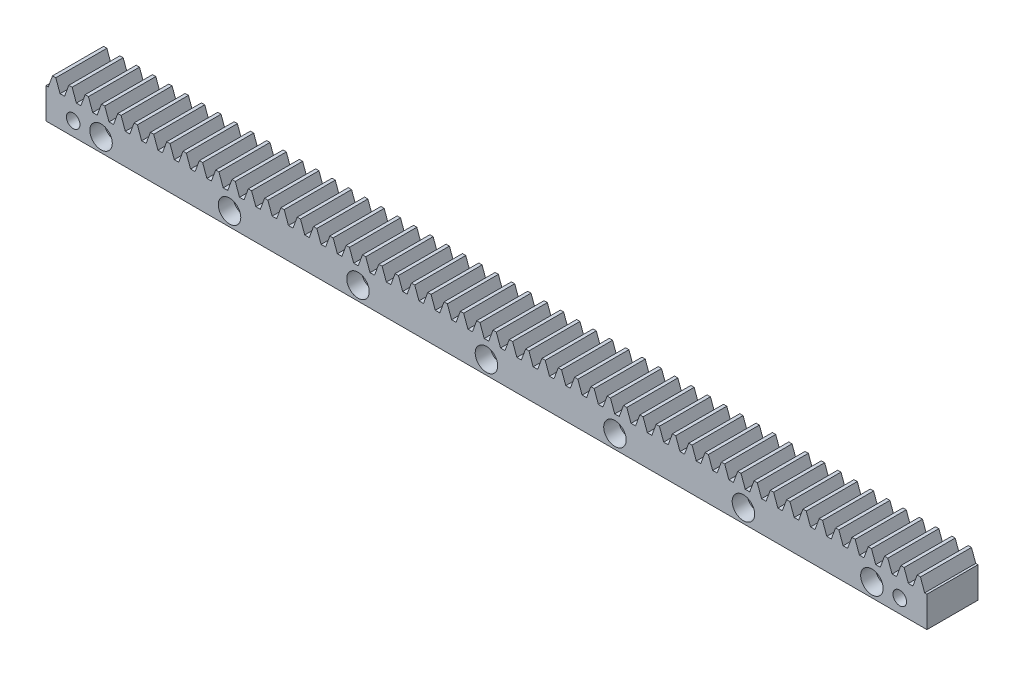
SolidWorks part; units mm, degrees
extrude "Blank" add sketch "BlankSke" against normal blind 59
sketch "BlankSke" plane through (0, 0, 0) normal (0, 0, 1) x (1, 0, 0)
  line L1 (0, 0) -> (1017.88, 0)
  line L2 (0, 0) -> (0, 49)
  line L3 (0, 49) -> (1017.88, 49)
  line L4 (1017.88, 0) -> (1017.88, 49)
  dimension "Length" = 1017.88
  dimension "Blank_height" = 49
ref_plane "Plane1" through (0, 0, 0) normal (0, 0, 1) x (1, 0, 0)
ref_plane "Plane2" through (0, 0, 0) normal (0, 1, 0) x (1, 0, 0)
ref_plane "Plane3" through (0, 0, 0) normal (1, 0, 0) x (0, 0, -1)
sketch "HoldingSke" plane through (0, 0, 0) normal (0, 1, 0) x (1, 0, 0)
  line L0 (0, 0) -> (0.0232, 0.165)
  line L1 (-15, 0) -> (100, 0) construction
  line L2 (0, 0) -> (-2.1039, 2.3779)
  line L3 (0, 0) -> (-11.863, 4.5341)
  line L4 (0, 0) -> (4.8292, 7.1596)
  line L5 (0, 0) -> (-23.7986, -8.8762)
  line L6 (0, 0) -> (-10.5278, -7.1032)
  line L9 (-71.009, 38.7566) -> (885.4854, 386.8921)
  line L10 (-76.2, 8.3779) -> (-33.2, 8.3779)
  line L11 (0, 0) -> (-59, 0)
  line L12 (-76.2, 101.6) -> (-75.993, 101.6)
  line L13 (24.9733, 27.94) -> (52.9518, 28.4284)
  line L14 (24.9733, 27.94) -> (24.9743, 27.94)
  line L15 (24.9733, 27.94) -> (100.4006, 29.5858)
  circle A0 centre (0, 0) radius 19.05
  circle A1 centre (0, 0) radius 21.5
  circle A2 centre (0, 0) radius 12.7
  dimension "MPH" = 43
  dimension "Diameter" = 38.1
  dimension "Num_teeth" = 56
  dimension "Pitch" = 0.1667
  dimension "Show_teeth" = 998
  dimension "Thickness" = 12.7
  dimension "Ap" = 20
  dimension "Pitch_height" = 43
  dimension "Width" = 59
  dimension "Backlash" = 0.207
  dimension "Addendum_fac" = 1
  dimension "Dedendum_fac" = 1.25
  dimension "Clearance_fac" = 0.25
  dimension "Dedendum_add" = 0.001
  dimension "Length" = 1017.88
  dimension "Module" = 6
sketch "TooCutSkeIll" plane through (0, 0, 0) normal (0, 0, 1) x (1, 0, 0)
  line L0 (-7.4597, 48.8421) -> (-2.9631, 36.4876)
  line L1 (-1.5526, 35.5) -> (1.5526, 35.5)
  line L2 (2.9631, 36.4876) -> (7.4597, 48.8421)
  line L3 (1017.88, 49) -> (0, 49) construction
  line L4 (0, 0) -> (0, 64.897) construction
  line L5 (-13.208, 43) -> (12.954, 43) construction
  line L6 (0, 0) -> (1017.88, 0) construction
  line L7 (5.3334, 43) -> (5.3334, 48.7463) construction
  line L8 (-5.3334, 43) -> (-5.3334, 48.7463) construction
  line L9 (7.6853, 49) -> (7.6853, 49.0254)
  line L10 (-7.6853, 49) -> (-7.6853, 49.0254)
  line L11 (-7.6853, 49.0254) -> (7.6853, 49.0254)
  arc A0 (1.5526, 35.5) -> (2.9631, 36.4876) centre (1.5526, 37.001) ccw
  arc A1 (-2.9631, 36.4876) -> (-1.5526, 35.5) centre (-1.5526, 37.001) ccw
  arc A2 (7.6853, 49) -> (7.4597, 48.8421) centre (7.6853, 48.76) ccw
  arc A3 (-7.4597, 48.8421) -> (-7.6853, 49) centre (-7.6853, 48.76) ccw
  dimension "Pitch_height" = 43
  dimension "Addendum_plus" = 6.0254
  dimension "Pressure_angle" = 20
  dimension "Gap_width" = 10.6668
  dimension "Dedendum" = 7.5
extrude "ToothCutIll" [suppressed] cut sketch "TooCutSkeIll" against normal through all
sketch "TooCutSkeSim" plane through (0, 0, 0) normal (0, 0, 1) x (1, 0, 0)
  line L0 (2.6036, 35.5) -> (-2.6036, 35.5)
  line L1 (7.5265, 49.0254) -> (2.6036, 35.5)
  line L2 (0, 17.4625) -> (0, 53.467) construction
  line L3 (7.5265, 49.0254) -> (-7.5265, 49.0254)
  line L6 (-7.5265, 49.0254) -> (-2.6036, 35.5)
  line L9 (-5.3334, 43) -> (5.3334, 43) construction
  line L10 (0, 0) -> (1017.88, 0) construction
  line L11 (5.3334, 43) -> (5.3334, 53.467) construction
  line L12 (-5.3334, 43) -> (-5.3334, 53.467) construction
  dimension "Pitch_height" = 43
  dimension "Addendum_plus" = 6.0254
  dimension "Pressure_angle" = 20
  dimension "Gap_width" = 10.6668
  dimension "Dedendum" = 7.5
extrude "ToothCutSim" cut sketch "TooCutSkeSim" against normal through all
pattern_linear "TeethCuts" count 55 spacing 18.8496 along (1, 0, 0) of "ToothCutIll", "ToothCutSim"
sketch "Sketch2" plane through (0, 0, 0) normal (0, 0, 1) x (1, 0, 0)
  line L0 (0, 35.5) -> (0, 0) construction
  line L1 (0, 0) -> (1017.88, 0) construction
  line L2 (1017.88, 0) -> (1017.88, 35.5) construction
  circle A0 centre (31.4, 16) radius 7.85
  circle A1 centre (986.48, 16) radius 7.85
  dimension "D1" = 15.7
  dimension "D5" = 15.7
  dimension "D2" = 31.4
  dimension "D3" = 16
  dimension "D4" = 16
  dimension "D6" = 31.4
extrude "Cut-Extrude1" cut sketch "Sketch2" against normal blind 202
sketch "Sketch3" plane through (0, 0, 0) normal (0, 0, 1) x (1, 0, 0)
  line L0 (0, 35.5) -> (0, 0) construction
  circle A0 centre (63.6, 16) radius 9
  dimension "D1" = 18
  dimension "D2" = 63.6
extrude "Cut-Extrude2" cut sketch "Sketch3" against normal blind 202
sketch "Sketch4" plane through (0, 0, 0) normal (0, 0, 1) x (1, 0, 0)
  circle A0 centre (63.6, 16) radius 13
  dimension "D1" = 26
extrude "Cut-Extrude3" cut sketch "Sketch4" against normal blind 17
sketch "Sketch5" plane through (0, 0, 0) normal (0, 0, 1) x (1, 0, 0)
  line L0 (63.6, 16) -> (31.4, 16)
  line L1 (986.48, 16) -> (954.28, 16)
  dimension "D1" = 32.2
  dimension "D2" = 32.2
pattern_linear "LPattern1" count 2 spacing 890.68 along (1, 0, 0) of "Cut-Extrude2", "Cut-Extrude3"
pattern_linear "LPattern2" count 6 spacing 148.4467 along (1, 0, 0) of "Cut-Extrude2", "Cut-Extrude3"
equation "' \"Module@HoldingSke\" = 6.35"
equation "' \"Num_teeth@HoldingSke\" = 12"
equation "' \"Ap@HoldingSke\" =  20"
equation "' \"Ap@HoldingSke\" = 20"
equation "' \"Width@HoldingSke\" = 0.25 * 25.4"
equation "' \"Show_teeth@HoldingSke\" = 500"
equation "' \"Backlash@HoldingSke\" = 0.009 * 25.4"
equation "' \"Addendum_fac@HoldingSke\" = 1.0"
equation "' \"Dedendum_fac@HoldingSke\" = 1.25"
equation "' \"Dedendum_add@HoldingSke\" = 0.00005 * 25.4"
equation "' \"Clearance_fac@HoldingSke\" = 0.25"
equation "' \"Pitch_height@HoldingSke\" = 1 * 25.4"
equation "' \"Length@HoldingSke\" = 4.71 * 25.4"
equation "\"Pitch@HoldingSke\" = 1 / \"Module@HoldingSke\""
equation "\"MPH@HoldingSke\" = \"Dedendum_fac@HoldingSke\" / \"Pitch@HoldingSke\" + 2 * \"Dedendum_add@HoldingSke\" + 0.002 * 25.4"
equation "\"MPH@HoldingSke\" = ((sgn( \"MPH@HoldingSke\" - \"Pitch_height@HoldingSke\")+1)*( \"MPH@HoldingSke\" - \"Pitch_height@HoldingSke\"))/2 + \"Pitch_height@HoldingSke\""
equation "\"Blank_height@BlankSke\" = \"Pitch_height@HoldingSke\" + \"Addendum_fac@HoldingSke\"  / \"Pitch@HoldingSke\" "
equation "\"Length@BlankSke\" =  \"Length@HoldingSke\""
equation "\"Face_width@Blank\" = \"Width@HoldingSke\""
equation "\"Pressure_angle@TooCutSkeIll\" = \"Ap@HoldingSke\""
equation "\"Addendum_plus@TooCutSkeIll\" =  \"Addendum_fac@HoldingSke\"  / \"Pitch@HoldingSke\" + 0.001 *25.4"
equation "\"Dedendum@TooCutSkeIll\" = \"Dedendum_fac@HoldingSke\"  / \"Pitch@HoldingSke\""
equation "\"Pitch_height@TooCutSkeIll\" =  \"MPH@HoldingSke\""
equation "\"Gap_width@TooCutSkeIll\" = 3.14159265 / 2 / \"Pitch@HoldingSke\" + 6 * \"Backlash@HoldingSke\""
equation "\"Pressure_angle@TooCutSkeSim\" = \"Ap@HoldingSke\""
equation "\"Addendum_plus@TooCutSkeSim\" =  \"Addendum_fac@HoldingSke\"  / \"Pitch@HoldingSke\" + 0.001 * 25.4"
equation "\"Dedendum@TooCutSkeSim\" = \"Dedendum_fac@HoldingSke\"  / \"Pitch@HoldingSke\""
equation "\"Pitch_height@TooCutSkeSim\" =  \"MPH@HoldingSke\""
equation "\"Gap_width@TooCutSkeSim\" = 3.14159265 / 2 / \"Pitch@HoldingSke\" + 6 * \"Backlash@HoldingSke\""
equation "\"Root_fillet@TooCutSkeIll\" = \"Clearance_fac@HoldingSke\" / \"Pitch@HoldingSke\" + \"Dedendum_add@HoldingSke\""
equation "\"Break_rad@TooCutSkeIll\" = 0.02 / \"Pitch@HoldingSke\" * 2"
equation "\"Linear_pitch@TeethCuts\" = 3.14159265 / \"Pitch@HoldingSke\""
equation "\"Num_teeth@HoldingSke\" = int( ( \"Length@HoldingSke\" + 0 ) / (3.14159265 / \"Pitch@HoldingSke\")) + 0.9999  + 1"
equation " \"Num_teeth@TeethCuts\" = int( \"Show_teeth@HoldingSke\" ) + 1"
equation " \"Num_teeth@TeethCuts\" = ((sgn( \"Num_teeth@TeethCuts\" - \"Num_teeth@HoldingSke\" )-1)*( \"Num_teeth@TeethCuts\" - \"Num_teeth@HoldingSke\" ))/-2+ \"Num_teeth@HoldingSke\""
equation " \"Num_teeth@TeethCuts\" = ((sgn( \"Num_teeth@TeethCuts\" - 2.0)+1)*( \"Num_teeth@TeethCuts\" - 2.0))/2 +2.0"
